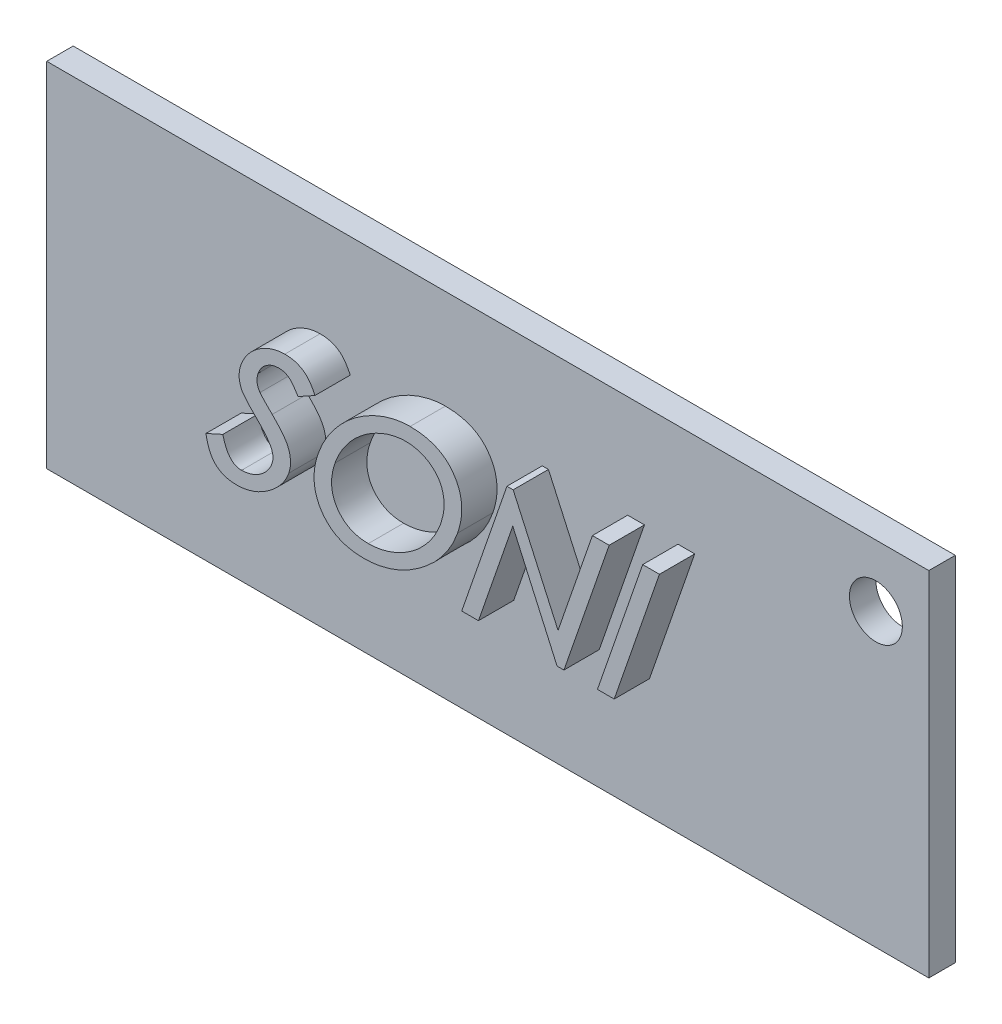
SolidWorks part; units mm, degrees
ref_plane "Front Plane" through (0, 0, 0) normal (0, 0, 1) x (1, 0, 0)
ref_plane "Top Plane" through (0, 0, 0) normal (0, 1, 0) x (1, 0, 0)
ref_plane "Right Plane" through (0, 0, 0) normal (1, 0, 0) x (0, 0, -1)
sketch "Sketch1" plane through (0, 0, 0) normal (0, 0, 1) x (1, 0, 0)
  line L1 (-25, -10) -> (25, -10)
  line L2 (-25, -10) -> (-25, 10)
  line L3 (-25, 10) -> (25, 10)
  line L4 (25, -10) -> (25, 10)
  line L5 (-25, -10) -> (25, 10) construction
  line L6 (-25, 10) -> (25, -10) construction
  point P0 (0, 0)
  dimension "D1" = 50
  dimension "D2" = 20
extrude "Boss-Extrude1" add sketch "Sketch1" along normal blind 1.5
sketch "Sketch2" plane through (0, 0, 1.5) normal (0, 0, 1) x (1, 0, 0)
  text T0 "SONI" font "Century Gothic" height in points 28
extrude "Boss-Extrude2" add sketch "Sketch2" along normal blind 2
sketch "Sketch3" plane through (0, 0, 1.5) normal (0, 0, 1) x (1, 0, 0)
  line L0 (25, -10) -> (25, 10) construction
  line L2 (25, 10) -> (-25, 10) construction
  circle A0 centre (22, 6.5) radius 1.5
  dimension "D1" = 3
  dimension "D2" = 3
  dimension "D3" = 3.5
extrude "Cut-Extrude1" cut sketch "Sketch3" against normal blind 2
